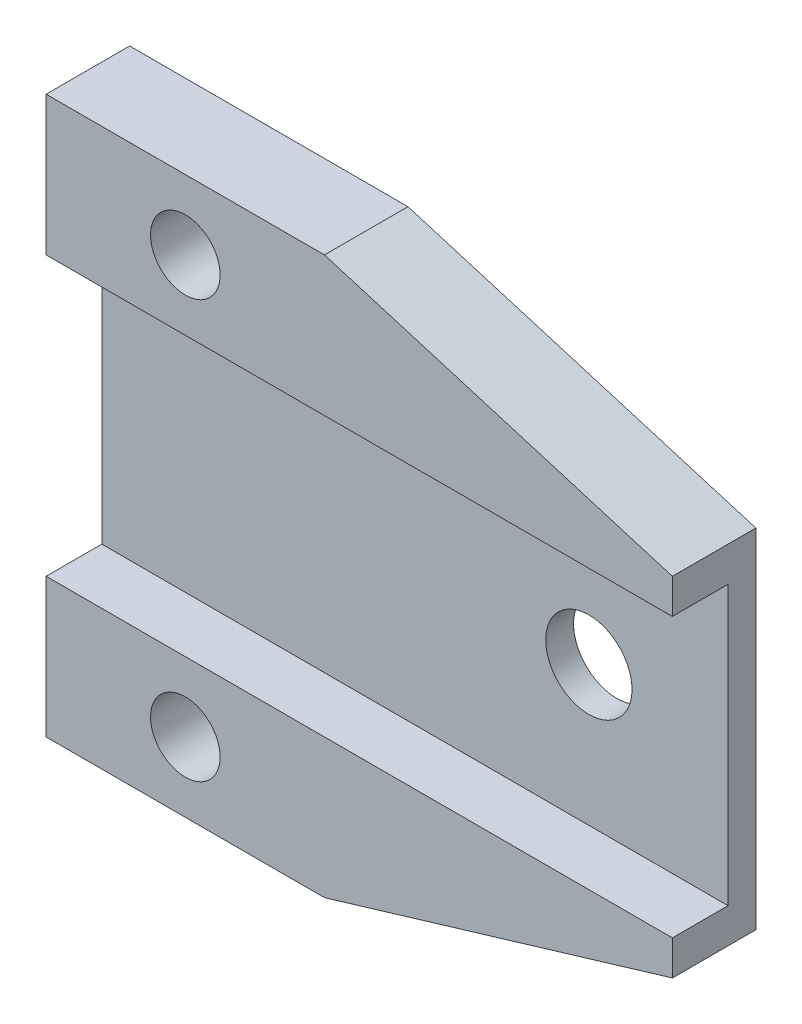
SolidWorks part; units mm, degrees
ref_plane "Front" through (0, 0, 0) normal (0, 0, 1) x (1, 0, 0)
ref_plane "Top" through (0, 0, 0) normal (0, 1, 0) x (1, 0, 0)
ref_plane "Right" through (0, 0, 0) normal (1, 0, 0) x (0, 0, -1)
sketch "Sketch1" plane through (0, 0, 0) normal (0, 0, 1) x (1, 0, 0)
  line L0 (10, 20) -> (35, 12.5)
  line L1 (-10, 20) -> (10, 20)
  line L2 (-10, 20) -> (-10, -20)
  line L3 (-10, -20) -> (10, -20)
  line L4 (10, -20) -> (35, -12.5)
  line L5 (0, 15) -> (0, 0) construction
  line L6 (0, 0) -> (0, -15) construction
  line L8 (35, 12.5) -> (35, -12.5)
  circle A0 centre (0, -15) radius 2.5
  circle A1 centre (0, 15) radius 2.5
  point P12 (-10, 0)
  point P13 (35, 0)
  point P14 (0, -20)
  dimension "D2" = 5
  dimension "D3" = 40
  dimension "D1" = 20
  dimension "D4" = 25
  dimension "D5" = 45
  dimension "D6" = 15
extrude "Boss-Extrude1" add sketch "Sketch1" along normal blind 6
sketch "Sketch2" plane through (35, 0, 0) normal (1, 0, 0) x (0, 0, -1)
  line L0 (-6, -12.5) -> (-6, 12.5) construction
  line L1 (-6, 10) -> (-2, 10)
  line L2 (-6, 10) -> (-6, -10)
  line L3 (-6, -10) -> (-2, -10)
  line L4 (-2, 10) -> (-2, -10)
  line L5 (-6, 12.5) -> (-6, 10) construction
  line L6 (-6, -10) -> (-6, -12.5) construction
  dimension "D1" = 20
  dimension "D2" = 4
extrude "Cut-Extrude1" cut sketch "Sketch2" against normal up to next
sketch "Sketch3" plane through (0, 0, 2) normal (0, 0, 1) x (1, 0, 0)
  circle A0 centre (25, 0) radius 3.1
  dimension "D2" = 6.2
  dimension "D1" = 25
extrude "Cut-Extrude2" cut sketch "Sketch3" against normal up to next
